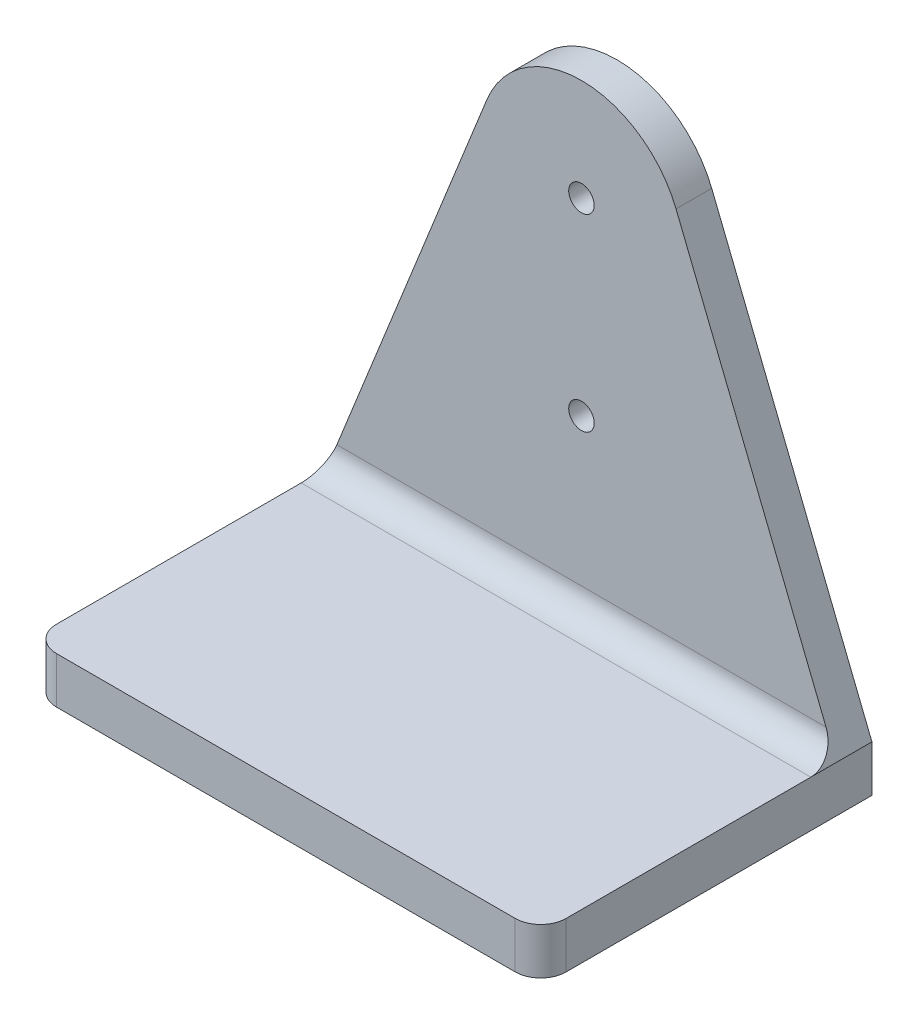
SolidWorks part; units mm, degrees
ref_plane "Front Plane" through (0, 0, 0) normal (0, 0, 1) x (1, 0, 0)
ref_plane "Top Plane" through (0, 0, 0) normal (0, 1, 0) x (1, 0, 0)
ref_plane "Right Plane" through (0, 0, 0) normal (1, 0, 0) x (0, 0, -1)
sketch "Sketch1" plane through (0, 0, 0) normal (0, 1, 0) x (1, 0, 0)
  line L1 (-50, 32.5) -> (50, 32.5)
  line L2 (-50, 32.5) -> (-50, -32.5)
  line L3 (-50, -32.5) -> (50, -32.5)
  line L4 (50, 32.5) -> (50, -32.5)
  line L5 (-50, 32.5) -> (50, -32.5) construction
  line L6 (-50, -32.5) -> (50, 32.5) construction
  point P0 (0, 0)
  dimension "D1" = 100
  dimension "D2" = 65
extrude "Extrude1" add sketch "Sketch1" along normal blind 9.1
sketch "Sketch3" plane through (0, 0, -32.5) normal (0, 0, -1) x (-1, 0, 0)
  line L0 (-50, 9.1) -> (-18.5614, 87.4481)
  line L1 (0, 0) -> (0, 80) construction
  line L2 (50, 9.1) -> (18.5614, 87.4481)
  line L3 (-50, 9.1) -> (50, 9.1)
  arc A0 (18.5614, 87.4481) -> (-18.5614, 87.4481) centre (0, 80) ccw
  dimension "D1" = 20
  dimension "D2" = 80
extrude "Extrude2" add sketch "Sketch3" against normal blind 7
hole_wizard "M6x1.0 Tapped Hole2" positions "Sketch7" profile "Sketch6" tap size "M6x1.0" standard "ANSI Metric"
sketch "Sketch7" plane through (0, 0, -25.5) normal (0, 0, 1) x (1, 0, 0)
  line L0 (-50, 0) -> (50, 0) construction
  arc A0 (18.5614, 87.4481) -> (-18.5614, 87.4481) centre (0, 80) ccw construction
  point P0 (0, 80)
  point P1 (0, 43)
  dimension "D2" = 43
sketch "Sketch6" plane through (0, 80, -25.5) normal (1, 0, 0) x (0, -1, 0)
  line L0 (0, 0) -> (0, 16.5022)
  line L1 (0, 16.5022) -> (2.5, 15)
  line L2 (2.5, 15) -> (2.5, 0)
  line L5 (2.5, 0) -> (0, 0)
  line L10 (0, 16.5022) -> (-2.5, 15) construction
  line L11 (0, -6.35) -> (0, 107.95) construction
  dimension "Tap Drill Dia." = 5
  dimension "Tap Drill Depth" = 15
  dimension "Drill Angle" = 118
cosmetic thread "Hole Thread3" parameters "D1"=7, "D2"=6
cosmetic thread "Hole Thread4" parameters "D1"=7, "D2"=6
fillet "Fillet1" radius 5 1 edges
fillet "Fillet2" radius 5 2 edges at (-50, 4.55, 32.5) (50, 4.55, 32.5)
